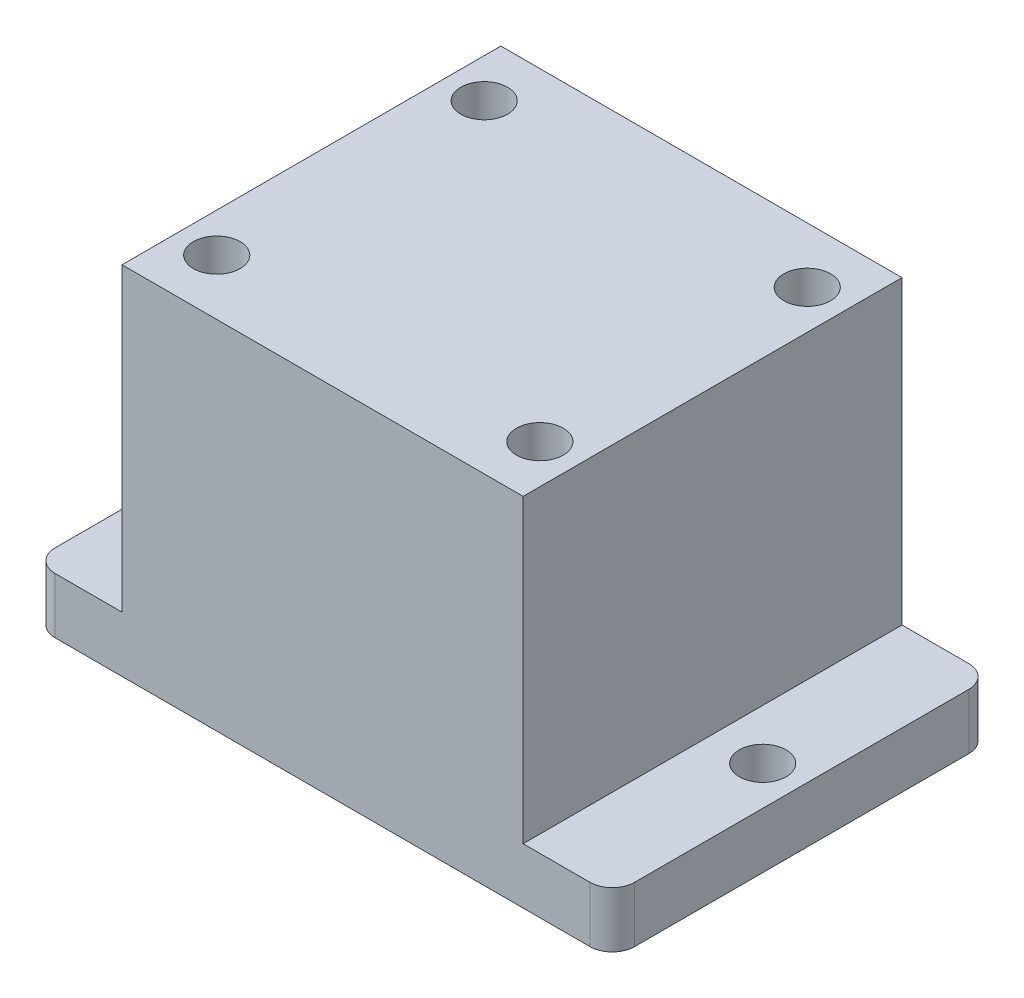
SolidWorks part; units mm, degrees
ref_plane "前视基准面" through (0, 0, 0) normal (0, 0, 1) x (1, 0, 0)
ref_plane "上视基准面" through (0, 0, 0) normal (0, 1, 0) x (1, 0, 0)
ref_plane "右视基准面" through (0, 0, 0) normal (1, 0, 0) x (0, 0, -1)
sketch "草图1" plane through (0, 0, 0) normal (0, 1, 0) x (1, 0, 0)
  line L0 (1, 17) -> (1, -17) construction
  line L1 (-25, 17) -> (27, 17)
  line L2 (-25, 17) -> (-25, -17)
  line L3 (-25, -17) -> (27, -17)
  line L4 (27, 17) -> (27, -17)
  circle A0 centre (-21.5, 0) radius 2.1
  circle A1 centre (23.5, 0) radius 2.1
  dimension "D7" = 4.2
  dimension "D1" = 52
  dimension "D2" = 34
  dimension "D3" = 25
  dimension "D4" = 17
  dimension "D5" = 22.5
  dimension "D6" = 17
extrude "凸台-拉伸1" add sketch "草图1" along normal blind 5
sketch "草图2" plane through (0, 5, 0) normal (0, 1, 0) x (1, 0, 0)
  line L0 (27, 17) -> (-25, 17) construction
  line L1 (-17, 17) -> (19, 17)
  line L2 (-17, 17) -> (-17, -17)
  line L3 (-17, -17) -> (19, -17)
  line L4 (19, 17) -> (19, -17)
  line L5 (-25, -17) -> (27, -17) construction
  line L6 (-25, 17) -> (-25, -17) construction
  dimension "D1" = 36
  dimension "D2" = 8
extrude "凸台-拉伸2" add sketch "草图2" along normal blind 27
sketch "草图3" plane through (0, 32, 0) normal (0, 1, 0) x (1, 0, 0)
  line L2 (-17, 17) -> (-17, -17) construction
  line L3 (19, 17) -> (-17, 17) construction
  circle A0 centre (-13.5, 12) radius 2.1
  circle A1 centre (15.5, 12) radius 2.1
  circle A2 centre (15.5, -12) radius 2.1
  circle A3 centre (-13.5, -12) radius 2.1
  dimension "D1" = 4.2
  dimension "D2" = 2
  dimension "D4" = 3.5
  dimension "D5" = 5
  dimension "D3" = 2
extrude "切除-拉伸1" cut sketch "草图3" against normal blind 10
fillet "圆角1" radius 2 1 edges at (-25, 2.5, -17)
fillet "圆角2" radius 2 1 edges at (-25, 2.5, 17)
fillet "圆角3" radius 2 1 edges at (27, 2.5, 17)
fillet "圆角4" radius 2 1 edges at (27, 2.5, -17)
